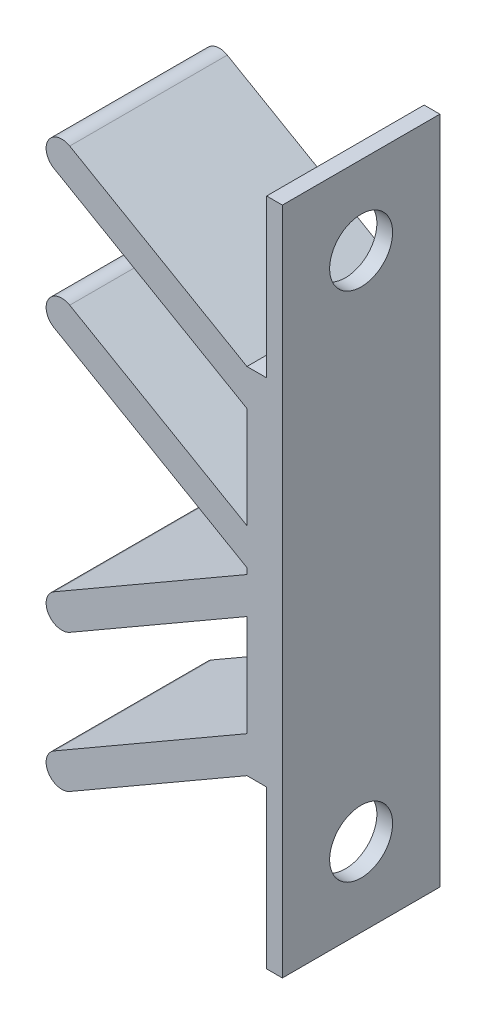
SolidWorks part; units mm, degrees
ref_plane "Front Plane" through (0, 0, 0) normal (1, 0, 0) x (0, 1, 0)
ref_plane "Top Plane" through (0, 0, 0) normal (0, 0, 1) x (0, 1, 0)
ref_plane "Right Plane" through (0, 0, 0) normal (0, 1, 0) x (-1, 0, 0)
sketch "Sketch1" plane through (0, 0, 0) normal (0, 0, 1) x (0, 1, 0)
  line L0 (-16.6492, -6.1754) -> (-16.6492, -5.3754)
  line L1 (-16.6492, -5.3754) -> (-8.6492, -5.3754)
  line L2 (-8.6492, -5.3754) -> (-8.6492, -4.3754)
  line L3 (-8.6492, -4.3754) -> (-13.8453, 4.6246)
  line L4 (-12.4597, 5.4246) -> (-6.8017, -4.3754)
  line L5 (-6.8017, -4.3754) -> (-1.6492, -4.3754)
  line L6 (-1.6492, -4.3754) -> (-6.8453, 4.6246)
  line L7 (-5.4597, 5.4246) -> (0.1983, -4.3754)
  line L8 (0.1983, -4.3754) -> (0.5033, -4.3754)
  line L9 (0.5033, -4.3754) -> (6.1613, 5.4246)
  line L10 (7.547, 4.6246) -> (2.3508, -4.3754)
  line L11 (2.3508, -4.3754) -> (7.5033, -4.3754)
  line L12 (7.5033, -4.3754) -> (13.1613, 5.4246)
  line L13 (14.547, 4.6246) -> (9.3508, -4.3754)
  line L14 (9.3508, -4.3754) -> (9.3508, -5.3754)
  line L15 (9.3508, -5.3754) -> (17.3508, -5.3754)
  line L16 (17.3508, -5.3754) -> (17.3508, -6.1754)
  line L17 (-16.6492, -6.1754) -> (17.3508, -6.1754)
  arc A0 (-12.4597, 5.4246) -> (-13.8453, 4.6246) centre (-13.1525, 5.0246) ccw
  arc A1 (-5.4597, 5.4246) -> (-6.8453, 4.6246) centre (-6.1525, 5.0246) ccw
  arc A2 (7.547, 4.6246) -> (6.1613, 5.4246) centre (6.8542, 5.0246) ccw
  arc A3 (14.547, 4.6246) -> (13.1613, 5.4246) centre (13.8542, 5.0246) ccw
extrude "Boss-Extrude1" add sketch "Sketch1" along normal blind 8
sketch "Sketch2" plane through (5.3754, 0, 0) normal (-1, 0, 0) x (0, -1, 0)
  line L0 (-17.3508, 8) -> (-17.3508, 0) construction
  line L1 (16.6492, 8) -> (16.6492, 0) construction
  line L2 (-13.1613, 8) -> (-7.5033, 8) construction
  line L3 (8.6492, 8) -> (16.6492, 8) construction
  circle A0 centre (-13.3508, 4) radius 1.6
  circle A1 centre (12.6492, 4) radius 1.6
  dimension "D1" = 3.2
  dimension "D2" = 3.2
  dimension "D3" = 4
  dimension "D4" = 4
  dimension "D5" = 4
  dimension "D6" = 4
extrude "Cut-Extrude1" cut sketch "Sketch2" against normal blind 9.5
